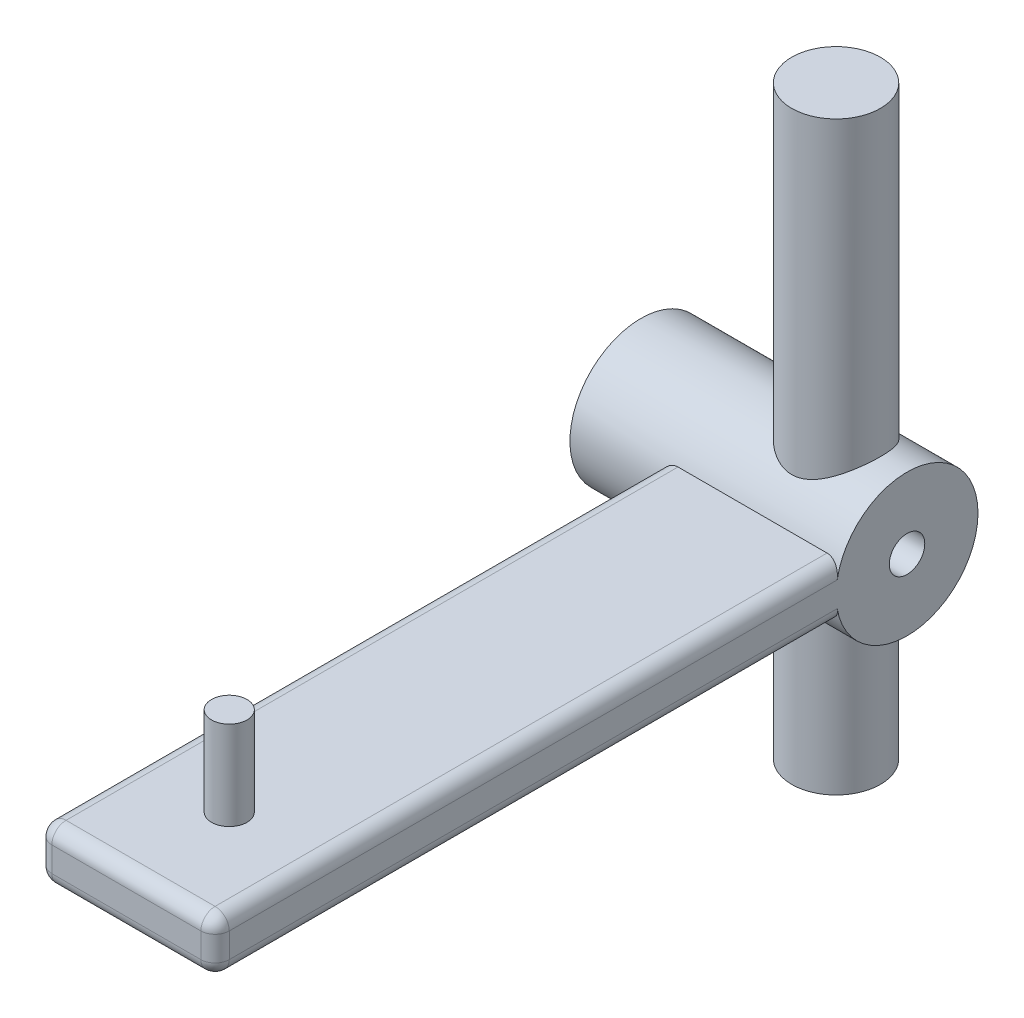
SolidWorks part; units mm, degrees
ref_plane "Front Plane" through (0, 0, 0) normal (0, 0, 1) x (1, 0, 0)
ref_plane "Top Plane" through (0, 0, 0) normal (0, 1, 0) x (1, 0, 0)
ref_plane "Right Plane" through (0, 0, 0) normal (1, 0, 0) x (0, 0, -1)
sketch "Sketch2" plane through (0, 0, 0) normal (1, 0, 0) x (0, 0, -1)
  circle A0 centre (0, 0) radius 4
  circle A1 centre (0, 0) radius 1
  dimension "D1" = 8
  dimension "D2" = 2
extrude "Boss-Extrude1" add sketch "Sketch2" along normal blind 15
sketch "Sketch3" plane through (15, 0, 0) normal (1, 0, 0) x (0, 0, -1)
  line L0 (0, 4) -> (0, -4) construction
  circle A0 centre (0, 0) radius 4 construction
ref_plane "Plane1" through (15, 4, 0) normal (0, 1, 0) x (1, 0, 0)
sketch "Sketch4" plane through (15, 4, 0) normal (0, 1, 0) x (1, 0, 0)
  line L0 (0, 4) -> (0, -4) construction
  line L1 (0, 0) -> (-4, 0) construction
  circle A0 centre (-4, 0) radius 2.5
  dimension "D2" = 5
  dimension "D1" = 4
extrude "Boss-Extrude2" add sketch "Sketch4" along normal blind 17 separate body
sketch "Sketch6" plane through (0, 4, 0) normal (0, -1, 0) x (1, 0, 0)
  circle A2 centre (11, 0) radius 2.5
  circle A3 centre (11, 0) radius 2.5
  dimension "D1" = 0
extrude "Boss-Extrude3" add sketch "Sketch6" along normal blind 16
sketch "Sketch8" plane through (15, 0, 0) normal (1, 0, 0) x (0, 0, -1)
  circle A2 centre (0, 0) radius 1
  circle A3 centre (0, 0) radius 1
  dimension "D1" = 0
extrude "Cut-Extrude1" cut sketch "Sketch8" against normal through all
sketch "Sketch9" plane through (15, 0, 0) normal (1, 0, 0) x (0, 0, -1)
  line L0 (-4, 0) -> (4, 0) construction
  circle A0 centre (0, 0) radius 4 construction
ref_plane "Plane3" through (15, 0, 4) normal (0, 0, 1) x (1, 0, 0)
sketch "Sketch10" plane through (15, 0, 4) normal (0, 0, 1) x (1, 0, 0)
  line L0 (0, 0) -> (-15, 0) construction
  line L1 (0, 4) -> (0, -4) construction
  line L2 (0, 1.5) -> (0, -1.5)
  line L3 (0, -1.5) -> (-10, -1.5)
  line L4 (-10, -1.5) -> (-10, 1.5)
  line L5 (-10, 1.5) -> (0, 1.5)
  line L6 (0, -1.5) -> (-10, 1.5) construction
  line L7 (-10, -1.5) -> (0, 1.5) construction
  point P9 (-5, 0)
  dimension "D1" = 3
  dimension "D2" = 10
extrude "Boss-Extrude4" add sketch "Sketch10" along normal blind 35 separate body
fillet "Fillet1" radius 0.8 8 edges at (5, 1.5, 21.5) (5, -1.5, 21.5) (10, -1.5, 39) (5, 0, 39) (10, 1.5, 39) (15, -1.5, 21.5) (15, 0, 39) (15, 1.5, 21.5)
sketch "Sketch11" plane through (15, 0, 4) normal (0, 0, 1) x (1, 0, 0)
  line L8 (-9.2, -1.5) -> (-0.8, -1.5)
  line L9 (-10, 0.7) -> (-10, -0.7)
  line L10 (-0.8, 1.5) -> (-9.2, 1.5)
  line L11 (0, -0.7) -> (0, 0.7)
  line L12 (-9.2, -1.5) -> (-0.8, -1.5)
  line L13 (-10, 0.7) -> (-10, -0.7)
  line L14 (-0.8, 1.5) -> (-9.2, 1.5)
  line L15 (0, -0.7) -> (0, 0.7)
  arc A8 (-10, -0.7) -> (-9.2, -1.5) centre (-9.2, -0.7) ccw
  arc A9 (-9.2, 1.5) -> (-10, 0.7) centre (-9.2, 0.7) ccw
  arc A10 (0, 0.7) -> (-0.8, 1.5) centre (-0.8, 0.7) ccw
  arc A11 (-0.8, -1.5) -> (0, -0.7) centre (-0.8, -0.7) ccw
  arc A12 (-10, -0.7) -> (-9.2, -1.5) centre (-9.2, -0.7) ccw
  arc A13 (-9.2, 1.5) -> (-10, 0.7) centre (-9.2, 0.7) ccw
  arc A14 (0, 0.7) -> (-0.8, 1.5) centre (-0.8, 0.7) ccw
  arc A15 (-0.8, -1.5) -> (0, -0.7) centre (-0.8, -0.7) ccw
  dimension "D1" = 0
extrude "Boss-Extrude5" add sketch "Sketch11" against normal up to surface (0.2919 mm away)
sketch "Sketch12" plane through (0, 1.5, 0) normal (0, 1, 0) x (1, 0, 0)
  line L0 (5.8, -38.2) -> (14.2, -38.2) construction
  circle A0 centre (10, -33.2) radius 1
  point P4 (0, 0)
  point P5 (10, -38.2)
  dimension "D1" = 2
  dimension "D2" = 5
extrude "Boss-Extrude6" add sketch "Sketch12" along normal blind 5
